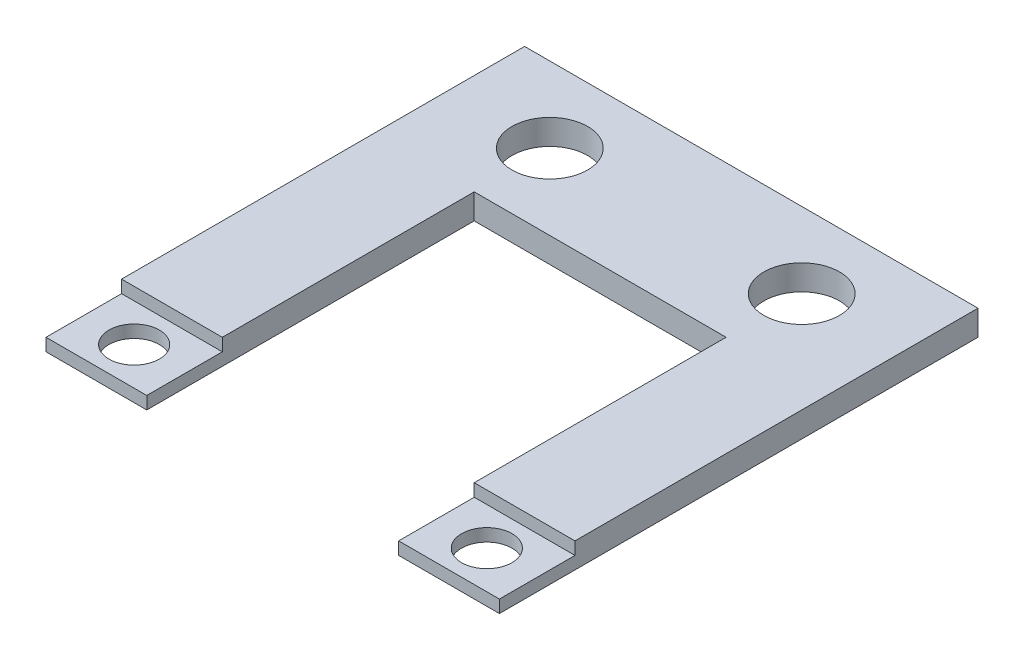
SolidWorks part; units mm, degrees
ref_plane "Front Plane" through (0, 0, 0) normal (0, 0, 1) x (1, 0, 0)
ref_plane "Top Plane" through (0, 0, 0) normal (0, 1, 0) x (1, 0, 0)
ref_plane "Right Plane" through (0, 0, 0) normal (1, 0, 0) x (0, 0, -1)
sketch "Sketch1" plane through (0, 0, 0) normal (0, 1, 0) x (1, 0, 0)
  line L1 (-14.2875, 15.0812) -> (14.2875, 15.0812)
  line L2 (-14.2875, 15.0812) -> (-14.2875, -15.0813)
  line L3 (-14.2875, -15.0813) -> (14.2875, -15.0812)
  line L4 (14.2875, 15.0812) -> (14.2875, -15.0812)
  line L5 (-7.9375, -15.0813) -> (7.9375, -15.0813)
  line L6 (-7.9375, -15.0813) -> (-7.9375, 5.5563)
  line L7 (-7.9375, 5.5563) -> (7.9375, 5.5563)
  line L8 (7.9375, -15.0813) -> (7.9375, 5.5563)
  point P4 (0, 15.0813)
  point P6 (-14.2875, 0)
  point P11 (0, 5.5563)
  point P12 (-10.4504, 8.3873)
  dimension "D1" = 28.575
  dimension "D2" = 30.1625
  dimension "D3" = 6.35
  dimension "D4" = 9.525
extrude "Boss-Extrude1" add sketch "Sketch1" along normal mid plane 1.5875 contours L8 L3 L4 L1 L2 L6 L7
sketch "Sketch2" plane through (0, 0.7937, 0) normal (0, 1, 0) x (1, 0, 0)
  line L0 (-7.9375, -15.0813) -> (-7.9375, 5.5563) construction
  line L1 (-14.2875, -15.0813) -> (-7.9375, -15.0813)
  line L2 (-14.2875, -15.0813) -> (-14.2875, -10.3188)
  line L3 (-14.2875, -10.3188) -> (-7.9375, -10.3188)
  line L4 (-7.9375, -15.0813) -> (-7.9375, -10.3188)
  line L5 (14.2875, 15.0812) -> (14.2875, -15.0812) construction
  line L6 (7.9375, -15.0812) -> (14.2875, -15.0812)
  line L7 (7.9375, -15.0812) -> (7.9375, -10.3188)
  line L8 (7.9375, -10.3188) -> (14.2875, -10.3188)
  line L9 (14.2875, -15.0812) -> (14.2875, -10.3188)
  dimension "D1" = 4.7625
extrude "Cut-Extrude1" cut sketch "Sketch2" against normal blind 0.7937
sketch "Sketch3" plane through (0, 0.7937, 0) normal (0, 1, 0) x (1, 0, 0)
  line L0 (-7.9375, -10.3188) -> (-14.2875, -10.3188) construction
  line L1 (-14.2875, -10.3188) -> (-14.2875, -15.0813) construction
  line L2 (0, -1000) -> (0, 49000) construction
  line L3 (-14.2875, 15.0812) -> (-14.2875, -10.3188) construction
  line L4 (-14.2875, 15.0812) -> (14.2875, 15.0812) construction
  circle A0 centre (-11.1125, -12.7) radius 1.5875
  circle A1 centre (-7.9375, 10.3187) radius 2.3813
  circle A2 centre (11.1125, -12.7) radius 1.5875
  circle A3 centre (7.9375, 10.3187) radius 2.3813
  point P6 (-11.1125, -10.3188)
  point P9 (-14.2875, -12.7)
  dimension "D1" = 3.175
  dimension "D2" = 4.7625
  dimension "D3" = 6.35
  dimension "D4" = 4.7625
extrude "Cut-Extrude2" cut sketch "Sketch3" against normal up to surface (1.5875 mm away) from surface at 0 up to face at (0, -0.7937, 2.3812) starting at face at (0, 0.7937, 0)
